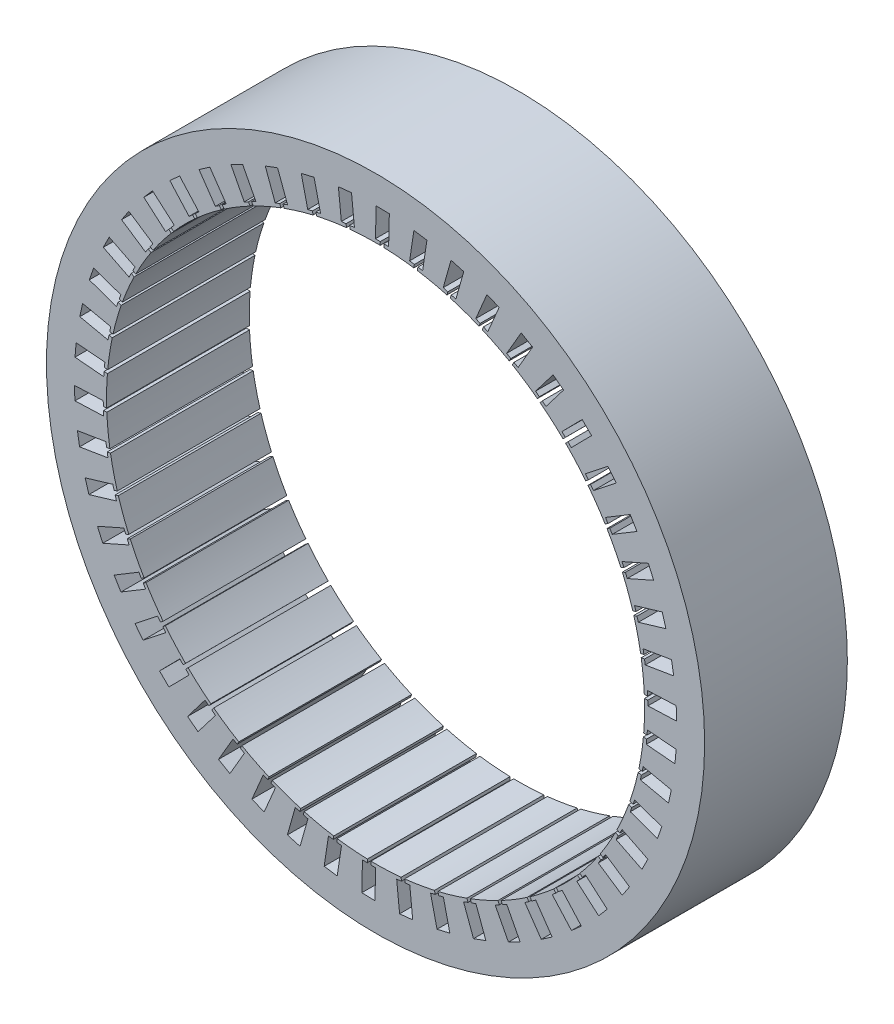
SolidWorks part; units mm, degrees
ref_plane "Спереди" through (0, 0, 0) normal (0, 0, 1) x (1, 0, 0)
ref_plane "Сверху" through (0, 0, 0) normal (0, 1, 0) x (1, 0, 0)
ref_plane "Справа" through (0, 0, 0) normal (1, 0, 0) x (0, 0, -1)
sketch "Эскиз1" plane through (0, 0, 0) normal (0, 0, 1) x (1, 0, 0)
  circle A0 centre (0, 0) radius 92.2462
  circle A1 centre (0, 0) radius 75.4
extrude "Rotor_stack" add sketch "Эскиз1" along normal blind 40 from offset 20
sketch "Эскиз2" plane through (0, 0, 0) normal (0, 0, 1) x (1, 0, 0)
  line L0 (74.5612, 2.4057) -> (76.2846, 2.4729)
  line L1 (76.2846, 2.4729) -> (76.3371, 1.1277)
  line L2 (76.3371, 1.1277) -> (84.4079, 1.4423)
  line L3 (84.4079, 1.4423) -> (84.2641, 5.1318)
  line L4 (84.2641, 5.1318) -> (76.1933, 4.8172)
  line L5 (76.1933, 4.8172) -> (76.2457, 3.4721)
  line L6 (76.2457, 3.4721) -> (74.5223, 3.4049)
  line L7 (74.5223, 3.4049) -> (74.5612, 2.4057)
  line L8 (73.6718, 11.7317) -> (75.3732, 12.0144)
  line L9 (75.3732, 12.0144) -> (75.5938, 10.6864)
  line L10 (75.5938, 10.6864) -> (83.5615, 12.01)
  line L11 (83.5615, 12.01) -> (82.9564, 15.6524)
  line L12 (82.9564, 15.6524) -> (74.9887, 14.3288)
  line L13 (74.9887, 14.3288) -> (75.2093, 13.0008)
  line L14 (75.2093, 13.0008) -> (73.5079, 12.7182)
  line L15 (73.5079, 12.7182) -> (73.6718, 11.7317)
  line L16 (71.6205, 20.8727) -> (73.273, 21.3664)
  line L17 (73.273, 21.3664) -> (73.6584, 20.0765)
  line L18 (73.6584, 20.0765) -> (81.3974, 22.3884)
  line L19 (81.3974, 22.3884) -> (80.3405, 25.9262)
  line L20 (80.3405, 25.9262) -> (72.6015, 23.6144)
  line L21 (72.6015, 23.6144) -> (72.9868, 22.3245)
  line L22 (72.9868, 22.3245) -> (71.3342, 21.8309)
  line L23 (71.3342, 21.8309) -> (71.6205, 20.8727)
  line L24 (68.4397, 29.6846) -> (70.0174, 30.3814)
  line L25 (70.0174, 30.3814) -> (70.5613, 29.1501)
  line L26 (70.5613, 29.1501) -> (77.9495, 32.4136)
  line L27 (77.9495, 32.4136) -> (76.4576, 35.7911)
  line L28 (76.4576, 35.7911) -> (69.0694, 32.5276)
  line L29 (69.0694, 32.5276) -> (69.6133, 31.2962)
  line L30 (69.6133, 31.2962) -> (68.0356, 30.5993)
  line L31 (68.0356, 30.5993) -> (68.4397, 29.6846)
  line L32 (64.1795, 38.0282) -> (65.6574, 38.9174)
  line L33 (65.6574, 38.9174) -> (66.3514, 37.7639)
  line L34 (66.3514, 37.7639) -> (73.2724, 41.9277)
  line L35 (73.2724, 41.9277) -> (71.3689, 45.0915)
  line L36 (71.3689, 45.0915) -> (64.448, 40.9278)
  line L37 (64.448, 40.9278) -> (65.1419, 39.7743)
  line L38 (65.1419, 39.7743) -> (63.664, 38.8851)
  line L39 (63.664, 38.8851) -> (64.1795, 38.0282)
  line L40 (58.9073, 45.7722) -> (60.2621, 46.8396)
  line L41 (60.2621, 46.8396) -> (61.0951, 45.7821)
  line L42 (61.0951, 45.7821) -> (67.4396, 50.7805)
  line L43 (67.4396, 50.7805) -> (65.1547, 53.6809)
  line L44 (65.1547, 53.6809) -> (58.8102, 48.6825)
  line L45 (58.8102, 48.6825) -> (59.6432, 47.6251)
  line L46 (59.6432, 47.6251) -> (58.2884, 46.5577)
  line L47 (58.2884, 46.5577) -> (58.9073, 45.7722)
  line L48 (52.706, 52.7943) -> (53.9163, 54.0231)
  line L49 (53.9163, 54.0231) -> (54.8754, 53.0784)
  line L50 (54.8754, 53.0784) -> (60.5434, 58.8325)
  line L51 (60.5434, 58.8325) -> (57.9129, 61.4236)
  line L52 (57.9129, 61.4236) -> (52.2449, 55.6695)
  line L53 (52.2449, 55.6695) -> (53.2039, 54.7248)
  line L54 (53.2039, 54.7248) -> (51.9936, 53.4961)
  line L55 (51.9936, 53.4961) -> (52.706, 52.7943)
  line L56 (45.6735, 58.9838) -> (46.7203, 60.3546)
  line L57 (46.7203, 60.3546) -> (47.7902, 59.5376)
  line L58 (47.7902, 59.5376) -> (52.6923, 65.9567)
  line L59 (52.6923, 65.9567) -> (49.7578, 68.1977)
  line L60 (49.7578, 68.1977) -> (44.8557, 61.7785)
  line L61 (44.8557, 61.7785) -> (45.9255, 60.9615)
  line L62 (45.9255, 60.9615) -> (44.8787, 59.5908)
  line L63 (44.8787, 59.5908) -> (45.6735, 58.9838)
  line L64 (37.9207, 64.2431) -> (38.7875, 65.7343)
  line L65 (38.7875, 65.7343) -> (39.9513, 65.0578)
  line L66 (39.9513, 65.0578) -> (44.0102, 72.0407)
  line L67 (44.0102, 72.0407) -> (40.818, 73.8963)
  line L68 (40.818, 73.8963) -> (36.7591, 66.9133)
  line L69 (36.7591, 66.9133) -> (37.9229, 66.2368)
  line L70 (37.9229, 66.2368) -> (37.0562, 64.7457)
  line L71 (37.0562, 64.7457) -> (37.9207, 64.2431)
  line L72 (29.5699, 68.4893) -> (30.2429, 70.0773)
  line L73 (30.2429, 70.0773) -> (31.4824, 69.552)
  line L74 (31.4824, 69.552) -> (34.6341, 76.9886)
  line L75 (34.6341, 76.9886) -> (31.2345, 78.4294)
  line L76 (31.2345, 78.4294) -> (28.0828, 70.9928)
  line L77 (28.0828, 70.9928) -> (29.3222, 70.4675)
  line L78 (29.3222, 70.4675) -> (28.6492, 68.8795)
  line L79 (28.6492, 68.8795) -> (29.5699, 68.4893)
  line L80 (20.7527, 71.6553) -> (21.2214, 73.3152)
  line L81 (21.2214, 73.3152) -> (22.5169, 72.9494)
  line L82 (22.5169, 72.9494) -> (24.7118, 80.7223)
  line L83 (24.7118, 80.7223) -> (21.1584, 81.7257)
  line L84 (21.1584, 81.7257) -> (18.9636, 73.9527)
  line L85 (18.9636, 73.9527) -> (20.2591, 73.5869)
  line L86 (20.2591, 73.5869) -> (19.7904, 71.9271)
  line L87 (19.7904, 71.9271) -> (20.7527, 71.6553)
  line L88 (11.6083, 73.6913) -> (11.8653, 75.3968)
  line L89 (11.8653, 75.3968) -> (13.1964, 75.1962)
  line L90 (13.1964, 75.1962) -> (14.3997, 83.183)
  line L91 (14.3997, 83.183) -> (10.7486, 83.7331)
  line L92 (10.7486, 83.7331) -> (9.5453, 75.7463)
  line L93 (9.5453, 75.7463) -> (10.8764, 75.5458)
  line L94 (10.8764, 75.5458) -> (10.6195, 73.8403)
  line L95 (10.6195, 73.8403) -> (11.6083, 73.6913)
  line L96 (2.2808, 74.5651) -> (2.322, 76.2894)
  line L97 (2.322, 76.2894) -> (3.6678, 76.2572)
  line L98 (3.6678, 76.2572) -> (3.8606, 84.3319)
  line L99 (3.8606, 84.3319) -> (0.1693, 84.42)
  line L100 (0.1693, 84.42) -> (-0.0235, 76.3454)
  line L101 (-0.0235, 76.3454) -> (1.3223, 76.3133)
  line L102 (1.3223, 76.3133) -> (1.2811, 74.589)
  line L103 (1.2811, 74.589) -> (2.2808, 74.5651)
  line L104 (-7.0827, 74.263) -> (-7.2579, 75.9788)
  line L105 (-7.2579, 75.9788) -> (-5.9187, 76.1156)
  line L106 (-5.9187, 76.1156) -> (-6.7394, 84.1507)
  line L107 (-6.7394, 84.1507) -> (-10.4126, 83.7756)
  line L108 (-10.4126, 83.7756) -> (-9.5919, 75.7404)
  line L109 (-9.5919, 75.7404) -> (-8.2527, 75.8772)
  line L110 (-8.2527, 75.8772) -> (-8.0775, 74.1614)
  line L111 (-8.0775, 74.1614) -> (-7.0827, 74.263)
  line L112 (-16.3344, 72.7897) -> (-16.7234, 74.4701)
  line L113 (-16.7234, 74.4701) -> (-15.4119, 74.7736)
  line L114 (-15.4119, 74.7736) -> (-17.2332, 82.6425)
  line L115 (-17.2332, 82.6425) -> (-20.8304, 81.8099)
  line L116 (-20.8304, 81.8099) -> (-19.0091, 73.941)
  line L117 (-19.0091, 73.941) -> (-17.6976, 74.2446)
  line L118 (-17.6976, 74.2446) -> (-17.3087, 72.5642)
  line L119 (-17.3087, 72.5642) -> (-16.3344, 72.7897)
  line L120 (-25.3286, 70.1685) -> (-25.9251, 71.7869)
  line L121 (-25.9251, 71.7869) -> (-24.662, 72.2524)
  line L122 (-24.662, 72.2524) -> (-27.4552, 79.831)
  line L123 (-27.4552, 79.831) -> (-30.9196, 78.5541)
  line L124 (-30.9196, 78.5541) -> (-28.1265, 70.9755)
  line L125 (-28.1265, 70.9755) -> (-26.8634, 71.441)
  line L126 (-26.8634, 71.441) -> (-26.2669, 69.8227)
  line L127 (-26.2669, 69.8227) -> (-25.3286, 70.1685)
  line L128 (-33.9233, 66.4407) -> (-34.7179, 67.9715)
  line L129 (-34.7179, 67.9715) -> (-33.5231, 68.5917)
  line L130 (-33.5231, 68.5917) -> (-37.2441, 75.7604)
  line L131 (-37.2441, 75.7604) -> (-40.5213, 74.0594)
  line L132 (-40.5213, 74.0594) -> (-36.8003, 66.8907)
  line L133 (-36.8003, 66.8907) -> (-35.6055, 67.5108)
  line L134 (-35.6055, 67.5108) -> (-34.8109, 65.98)
  line L135 (-34.8109, 65.98) -> (-33.9233, 66.4407)
  line L136 (-41.9831, 61.6651) -> (-42.9633, 63.0842)
  line L137 (-42.9633, 63.0842) -> (-41.8556, 63.8493)
  line L138 (-41.8556, 63.8493) -> (-46.4458, 70.4951)
  line L139 (-46.4458, 70.4951) -> (-49.4839, 68.3968)
  line L140 (-49.4839, 68.3968) -> (-44.8937, 61.7509)
  line L141 (-44.8937, 61.7509) -> (-43.7861, 62.5159)
  line L142 (-43.7861, 62.5159) -> (-42.8059, 61.0968)
  line L143 (-42.8059, 61.0968) -> (-41.9831, 61.6651)
  line L144 (-49.3807, 55.917) -> (-50.531, 57.2021)
  line L145 (-50.531, 57.2021) -> (-49.528, 58.0999)
  line L146 (-49.528, 58.0999) -> (-54.9149, 64.118)
  line L147 (-54.9149, 64.118) -> (-57.666, 61.6555)
  line L148 (-57.666, 61.6555) -> (-52.2792, 55.6373)
  line L149 (-52.2792, 55.6373) -> (-51.2761, 56.5351)
  line L150 (-51.2761, 56.5351) -> (-50.1258, 55.25)
  line L151 (-50.1258, 55.25) -> (-49.3807, 55.917)
  line L152 (-55.9996, 49.287) -> (-57.3019, 50.4178)
  line L153 (-57.3019, 50.4178) -> (-56.4193, 51.4343)
  line L154 (-56.4193, 51.4343) -> (-62.518, 56.7298)
  line L155 (-62.518, 56.7298) -> (-64.9388, 53.9418)
  line L156 (-64.9388, 53.9418) -> (-58.8401, 48.6463)
  line L157 (-58.8401, 48.6463) -> (-57.9575, 49.6627)
  line L158 (-57.9575, 49.6627) -> (-56.6552, 48.5319)
  line L159 (-56.6552, 48.5319) -> (-55.9996, 49.287)
  line L160 (-61.7353, 41.8797) -> (-63.1691, 42.8384)
  line L161 (-63.1691, 42.8384) -> (-62.4208, 43.9575)
  line L162 (-62.4208, 43.9575) -> (-69.1352, 48.4469)
  line L163 (-69.1352, 48.4469) -> (-71.1875, 45.3775)
  line L164 (-71.1875, 45.3775) -> (-64.4731, 40.8881)
  line L165 (-64.4731, 40.8881) -> (-63.7249, 42.0071)
  line L166 (-63.7249, 42.0071) -> (-62.2911, 41.0484)
  line L167 (-62.2911, 41.0484) -> (-61.7353, 41.8797)
  line L168 (-66.4974, 33.812) -> (-68.04, 34.5834)
  line L169 (-68.04, 34.5834) -> (-67.438, 35.7874)
  line L170 (-67.438, 35.7874) -> (-74.662, 39.3999)
  line L171 (-74.662, 39.3999) -> (-76.3134, 36.0975)
  line L172 (-76.3134, 36.0975) -> (-69.0894, 32.485)
  line L173 (-69.0894, 32.485) -> (-68.4873, 33.689)
  line L174 (-68.4873, 33.689) -> (-66.9447, 32.9176)
  line L175 (-66.9447, 32.9176) -> (-66.4974, 33.812)
  line L176 (-70.2108, 25.2111) -> (-71.838, 25.7831)
  line L177 (-71.838, 25.7831) -> (-71.3916, 27.053)
  line L178 (-71.3916, 27.053) -> (-79.0114, 29.7316)
  line L179 (-79.0114, 29.7316) -> (-80.2359, 26.2483)
  line L180 (-80.2359, 26.2483) -> (-72.6161, 23.5697)
  line L181 (-72.6161, 23.5697) -> (-72.1696, 24.8396)
  line L182 (-72.1696, 24.8396) -> (-70.5425, 24.2677)
  line L183 (-70.5425, 24.2677) -> (-70.2108, 25.2111)
  line L184 (-72.817, 16.2125) -> (-74.503, 16.5761)
  line L185 (-74.503, 16.5761) -> (-74.2193, 17.892)
  line L186 (-74.2193, 17.892) -> (-82.1147, 19.5944)
  line L187 (-82.1147, 19.5944) -> (-82.893, 15.9851)
  line L188 (-82.893, 15.9851) -> (-74.9975, 14.2826)
  line L189 (-74.9975, 14.2826) -> (-74.7138, 15.5985)
  line L190 (-74.7138, 15.5985) -> (-73.0278, 15.235)
  line L191 (-73.0278, 15.235) -> (-72.817, 16.2125)
  line L192 (-74.2748, 6.9583) -> (-75.993, 7.1077)
  line L193 (-75.993, 7.1077) -> (-75.8765, 8.4487)
  line L194 (-75.8765, 8.4487) -> (-83.9231, 9.1482)
  line L195 (-83.9231, 9.1482) -> (-84.2428, 5.4698)
  line L196 (-84.2428, 5.4698) -> (-76.1962, 4.7703)
  line L197 (-76.1962, 4.7703) -> (-76.0796, 6.1114)
  line L198 (-76.0796, 6.1114) -> (-74.3614, 5.962)
  line L199 (-74.3614, 5.962) -> (-74.2748, 6.9583)
  line L200 (-74.5612, -2.4057) -> (-76.2846, -2.4729)
  line L201 (-76.2846, -2.4729) -> (-76.3371, -1.1277)
  line L202 (-76.3371, -1.1277) -> (-84.4079, -1.4423)
  line L203 (-84.4079, -1.4423) -> (-84.2641, -5.1318)
  line L204 (-84.2641, -5.1318) -> (-76.1933, -4.8172)
  line L205 (-76.1933, -4.8172) -> (-76.2457, -3.4721)
  line L206 (-76.2457, -3.4721) -> (-74.5223, -3.4049)
  line L207 (-74.5223, -3.4049) -> (-74.5612, -2.4057)
  line L208 (-73.6718, -11.7317) -> (-75.3732, -12.0144)
  line L209 (-75.3732, -12.0144) -> (-75.5938, -10.6864)
  line L210 (-75.5938, -10.6864) -> (-83.5615, -12.01)
  line L211 (-83.5615, -12.01) -> (-82.9564, -15.6524)
  line L212 (-82.9564, -15.6524) -> (-74.9887, -14.3288)
  line L213 (-74.9887, -14.3288) -> (-75.2093, -13.0008)
  line L214 (-75.2093, -13.0008) -> (-73.5079, -12.7182)
  line L215 (-73.5079, -12.7182) -> (-73.6718, -11.7317)
  line L216 (-71.6205, -20.8727) -> (-73.273, -21.3664)
  line L217 (-73.273, -21.3664) -> (-73.6584, -20.0765)
  line L218 (-73.6584, -20.0765) -> (-81.3974, -22.3884)
  line L219 (-81.3974, -22.3884) -> (-80.3405, -25.9262)
  line L220 (-80.3405, -25.9262) -> (-72.6015, -23.6144)
  line L221 (-72.6015, -23.6144) -> (-72.9868, -22.3245)
  line L222 (-72.9868, -22.3245) -> (-71.3342, -21.8309)
  line L223 (-71.3342, -21.8309) -> (-71.6205, -20.8727)
  line L224 (-68.4397, -29.6846) -> (-70.0174, -30.3814)
  line L225 (-70.0174, -30.3814) -> (-70.5613, -29.1501)
  line L226 (-70.5613, -29.1501) -> (-77.9495, -32.4136)
  line L227 (-77.9495, -32.4136) -> (-76.4576, -35.7911)
  line L228 (-76.4576, -35.7911) -> (-69.0694, -32.5276)
  line L229 (-69.0694, -32.5276) -> (-69.6133, -31.2962)
  line L230 (-69.6133, -31.2962) -> (-68.0356, -30.5993)
  line L231 (-68.0356, -30.5993) -> (-68.4397, -29.6846)
  line L232 (-64.1795, -38.0282) -> (-65.6574, -38.9174)
  line L233 (-65.6574, -38.9174) -> (-66.3514, -37.7639)
  line L234 (-66.3514, -37.7639) -> (-73.2724, -41.9277)
  line L235 (-73.2724, -41.9277) -> (-71.3689, -45.0915)
  line L236 (-71.3689, -45.0915) -> (-64.448, -40.9278)
  line L237 (-64.448, -40.9278) -> (-65.1419, -39.7743)
  line L238 (-65.1419, -39.7743) -> (-63.664, -38.8851)
  line L239 (-63.664, -38.8851) -> (-64.1795, -38.0282)
  line L240 (-58.9073, -45.7722) -> (-60.2621, -46.8396)
  line L241 (-60.2621, -46.8396) -> (-61.0951, -45.7821)
  line L242 (-61.0951, -45.7821) -> (-67.4396, -50.7805)
  line L243 (-67.4396, -50.7805) -> (-65.1547, -53.6809)
  line L244 (-65.1547, -53.6809) -> (-58.8102, -48.6825)
  line L245 (-58.8102, -48.6825) -> (-59.6432, -47.6251)
  line L246 (-59.6432, -47.6251) -> (-58.2884, -46.5577)
  line L247 (-58.2884, -46.5577) -> (-58.9073, -45.7722)
  line L248 (-52.706, -52.7943) -> (-53.9163, -54.0231)
  line L249 (-53.9163, -54.0231) -> (-54.8754, -53.0784)
  line L250 (-54.8754, -53.0784) -> (-60.5434, -58.8325)
  line L251 (-60.5434, -58.8325) -> (-57.9129, -61.4236)
  line L252 (-57.9129, -61.4236) -> (-52.2449, -55.6695)
  line L253 (-52.2449, -55.6695) -> (-53.2039, -54.7248)
  line L254 (-53.2039, -54.7248) -> (-51.9936, -53.4961)
  line L255 (-51.9936, -53.4961) -> (-52.706, -52.7943)
  line L256 (-45.6735, -58.9838) -> (-46.7203, -60.3546)
  line L257 (-46.7203, -60.3546) -> (-47.7902, -59.5376)
  line L258 (-47.7902, -59.5376) -> (-52.6923, -65.9567)
  line L259 (-52.6923, -65.9567) -> (-49.7578, -68.1977)
  line L260 (-49.7578, -68.1977) -> (-44.8557, -61.7785)
  line L261 (-44.8557, -61.7785) -> (-45.9255, -60.9615)
  line L262 (-45.9255, -60.9615) -> (-44.8787, -59.5908)
  line L263 (-44.8787, -59.5908) -> (-45.6735, -58.9838)
  line L264 (-37.9207, -64.2431) -> (-38.7875, -65.7343)
  line L265 (-38.7875, -65.7343) -> (-39.9513, -65.0578)
  line L266 (-39.9513, -65.0578) -> (-44.0102, -72.0407)
  line L267 (-44.0102, -72.0407) -> (-40.818, -73.8963)
  line L268 (-40.818, -73.8963) -> (-36.7591, -66.9133)
  line L269 (-36.7591, -66.9133) -> (-37.9229, -66.2368)
  line L270 (-37.9229, -66.2368) -> (-37.0562, -64.7457)
  line L271 (-37.0562, -64.7457) -> (-37.9207, -64.2431)
  line L272 (-29.5699, -68.4893) -> (-30.2429, -70.0773)
  line L273 (-30.2429, -70.0773) -> (-31.4824, -69.552)
  line L274 (-31.4824, -69.552) -> (-34.6341, -76.9886)
  line L275 (-34.6341, -76.9886) -> (-31.2345, -78.4294)
  line L276 (-31.2345, -78.4294) -> (-28.0828, -70.9928)
  line L277 (-28.0828, -70.9928) -> (-29.3222, -70.4675)
  line L278 (-29.3222, -70.4675) -> (-28.6492, -68.8795)
  line L279 (-28.6492, -68.8795) -> (-29.5699, -68.4893)
  line L280 (-20.7527, -71.6553) -> (-21.2214, -73.3152)
  line L281 (-21.2214, -73.3152) -> (-22.5169, -72.9494)
  line L282 (-22.5169, -72.9494) -> (-24.7118, -80.7223)
  line L283 (-24.7118, -80.7223) -> (-21.1584, -81.7257)
  line L284 (-21.1584, -81.7257) -> (-18.9636, -73.9527)
  line L285 (-18.9636, -73.9527) -> (-20.2591, -73.5869)
  line L286 (-20.2591, -73.5869) -> (-19.7904, -71.9271)
  line L287 (-19.7904, -71.9271) -> (-20.7527, -71.6553)
  line L288 (-11.6083, -73.6913) -> (-11.8653, -75.3968)
  line L289 (-11.8653, -75.3968) -> (-13.1964, -75.1962)
  line L290 (-13.1964, -75.1962) -> (-14.3997, -83.183)
  line L291 (-14.3997, -83.183) -> (-10.7486, -83.7331)
  line L292 (-10.7486, -83.7331) -> (-9.5453, -75.7463)
  line L293 (-9.5453, -75.7463) -> (-10.8764, -75.5458)
  line L294 (-10.8764, -75.5458) -> (-10.6195, -73.8403)
  line L295 (-10.6195, -73.8403) -> (-11.6083, -73.6913)
  line L296 (-2.2808, -74.5651) -> (-2.322, -76.2894)
  line L297 (-2.322, -76.2894) -> (-3.6678, -76.2572)
  line L298 (-3.6678, -76.2572) -> (-3.8606, -84.3319)
  line L299 (-3.8606, -84.3319) -> (-0.1693, -84.42)
  line L300 (-0.1693, -84.42) -> (0.0235, -76.3454)
  line L301 (0.0235, -76.3454) -> (-1.3223, -76.3133)
  line L302 (-1.3223, -76.3133) -> (-1.2811, -74.589)
  line L303 (-1.2811, -74.589) -> (-2.2808, -74.5651)
  line L304 (7.0827, -74.263) -> (7.2579, -75.9788)
  line L305 (7.2579, -75.9788) -> (5.9187, -76.1156)
  line L306 (5.9187, -76.1156) -> (6.7394, -84.1507)
  line L307 (6.7394, -84.1507) -> (10.4126, -83.7756)
  line L308 (10.4126, -83.7756) -> (9.5919, -75.7404)
  line L309 (9.5919, -75.7404) -> (8.2527, -75.8772)
  line L310 (8.2527, -75.8772) -> (8.0775, -74.1614)
  line L311 (8.0775, -74.1614) -> (7.0827, -74.263)
  line L312 (16.3344, -72.7897) -> (16.7234, -74.4701)
  line L313 (16.7234, -74.4701) -> (15.4119, -74.7736)
  line L314 (15.4119, -74.7736) -> (17.2332, -82.6425)
  line L315 (17.2332, -82.6425) -> (20.8304, -81.8099)
  line L316 (20.8304, -81.8099) -> (19.0091, -73.941)
  line L317 (19.0091, -73.941) -> (17.6976, -74.2446)
  line L318 (17.6976, -74.2446) -> (17.3087, -72.5642)
  line L319 (17.3087, -72.5642) -> (16.3344, -72.7897)
  line L320 (25.3286, -70.1685) -> (25.9251, -71.7869)
  line L321 (25.9251, -71.7869) -> (24.662, -72.2524)
  line L322 (24.662, -72.2524) -> (27.4552, -79.831)
  line L323 (27.4552, -79.831) -> (30.9196, -78.5541)
  line L324 (30.9196, -78.5541) -> (28.1265, -70.9755)
  line L325 (28.1265, -70.9755) -> (26.8634, -71.441)
  line L326 (26.8634, -71.441) -> (26.2669, -69.8227)
  line L327 (26.2669, -69.8227) -> (25.3286, -70.1685)
  line L328 (33.9233, -66.4407) -> (34.7179, -67.9715)
  line L329 (34.7179, -67.9715) -> (33.5231, -68.5917)
  line L330 (33.5231, -68.5917) -> (37.2441, -75.7604)
  line L331 (37.2441, -75.7604) -> (40.5213, -74.0594)
  line L332 (40.5213, -74.0594) -> (36.8003, -66.8907)
  line L333 (36.8003, -66.8907) -> (35.6055, -67.5108)
  line L334 (35.6055, -67.5108) -> (34.8109, -65.98)
  line L335 (34.8109, -65.98) -> (33.9233, -66.4407)
  line L336 (41.9831, -61.6651) -> (42.9633, -63.0842)
  line L337 (42.9633, -63.0842) -> (41.8556, -63.8493)
  line L338 (41.8556, -63.8493) -> (46.4458, -70.4951)
  line L339 (46.4458, -70.4951) -> (49.4839, -68.3968)
  line L340 (49.4839, -68.3968) -> (44.8937, -61.7509)
  line L341 (44.8937, -61.7509) -> (43.7861, -62.5159)
  line L342 (43.7861, -62.5159) -> (42.8059, -61.0968)
  line L343 (42.8059, -61.0968) -> (41.9831, -61.6651)
  line L344 (49.3807, -55.917) -> (50.531, -57.2021)
  line L345 (50.531, -57.2021) -> (49.528, -58.0999)
  line L346 (49.528, -58.0999) -> (54.9149, -64.118)
  line L347 (54.9149, -64.118) -> (57.666, -61.6555)
  line L348 (57.666, -61.6555) -> (52.2792, -55.6373)
  line L349 (52.2792, -55.6373) -> (51.2761, -56.5351)
  line L350 (51.2761, -56.5351) -> (50.1258, -55.25)
  line L351 (50.1258, -55.25) -> (49.3807, -55.917)
  line L352 (55.9996, -49.287) -> (57.3019, -50.4178)
  line L353 (57.3019, -50.4178) -> (56.4193, -51.4343)
  line L354 (56.4193, -51.4343) -> (62.518, -56.7298)
  line L355 (62.518, -56.7298) -> (64.9388, -53.9418)
  line L356 (64.9388, -53.9418) -> (58.8401, -48.6463)
  line L357 (58.8401, -48.6463) -> (57.9575, -49.6627)
  line L358 (57.9575, -49.6627) -> (56.6552, -48.5319)
  line L359 (56.6552, -48.5319) -> (55.9996, -49.287)
  line L360 (61.7353, -41.8797) -> (63.1691, -42.8384)
  line L361 (63.1691, -42.8384) -> (62.4208, -43.9575)
  line L362 (62.4208, -43.9575) -> (69.1352, -48.4469)
  line L363 (69.1352, -48.4469) -> (71.1875, -45.3775)
  line L364 (71.1875, -45.3775) -> (64.4731, -40.8881)
  line L365 (64.4731, -40.8881) -> (63.7249, -42.0071)
  line L366 (63.7249, -42.0071) -> (62.2911, -41.0484)
  line L367 (62.2911, -41.0484) -> (61.7353, -41.8797)
  line L368 (66.4974, -33.812) -> (68.04, -34.5834)
  line L369 (68.04, -34.5834) -> (67.438, -35.7874)
  line L370 (67.438, -35.7874) -> (74.662, -39.3999)
  line L371 (74.662, -39.3999) -> (76.3134, -36.0975)
  line L372 (76.3134, -36.0975) -> (69.0894, -32.485)
  line L373 (69.0894, -32.485) -> (68.4873, -33.689)
  line L374 (68.4873, -33.689) -> (66.9447, -32.9176)
  line L375 (66.9447, -32.9176) -> (66.4974, -33.812)
  line L376 (70.2108, -25.2111) -> (71.838, -25.7831)
  line L377 (71.838, -25.7831) -> (71.3916, -27.053)
  line L378 (71.3916, -27.053) -> (79.0114, -29.7316)
  line L379 (79.0114, -29.7316) -> (80.2359, -26.2483)
  line L380 (80.2359, -26.2483) -> (72.6161, -23.5697)
  line L381 (72.6161, -23.5697) -> (72.1696, -24.8396)
  line L382 (72.1696, -24.8396) -> (70.5425, -24.2677)
  line L383 (70.5425, -24.2677) -> (70.2108, -25.2111)
  line L384 (72.817, -16.2125) -> (74.503, -16.5761)
  line L385 (74.503, -16.5761) -> (74.2193, -17.892)
  line L386 (74.2193, -17.892) -> (82.1147, -19.5944)
  line L387 (82.1147, -19.5944) -> (82.893, -15.9851)
  line L388 (82.893, -15.9851) -> (74.9975, -14.2826)
  line L389 (74.9975, -14.2826) -> (74.7138, -15.5985)
  line L390 (74.7138, -15.5985) -> (73.0278, -15.235)
  line L391 (73.0278, -15.235) -> (72.817, -16.2125)
  line L392 (74.2748, -6.9583) -> (75.993, -7.1077)
  line L393 (75.993, -7.1077) -> (75.8765, -8.4487)
  line L394 (75.8765, -8.4487) -> (83.9231, -9.1482)
  line L395 (83.9231, -9.1482) -> (84.2428, -5.4698)
  line L396 (84.2428, -5.4698) -> (76.1962, -4.7703)
  line L397 (76.1962, -4.7703) -> (76.0796, -6.1114)
  line L398 (76.0796, -6.1114) -> (74.3614, -5.962)
  line L399 (74.3614, -5.962) -> (74.2748, -6.9583)
extrude "Rotor_50_slots" cut sketch "Эскиз2" against normal mid plane 42
